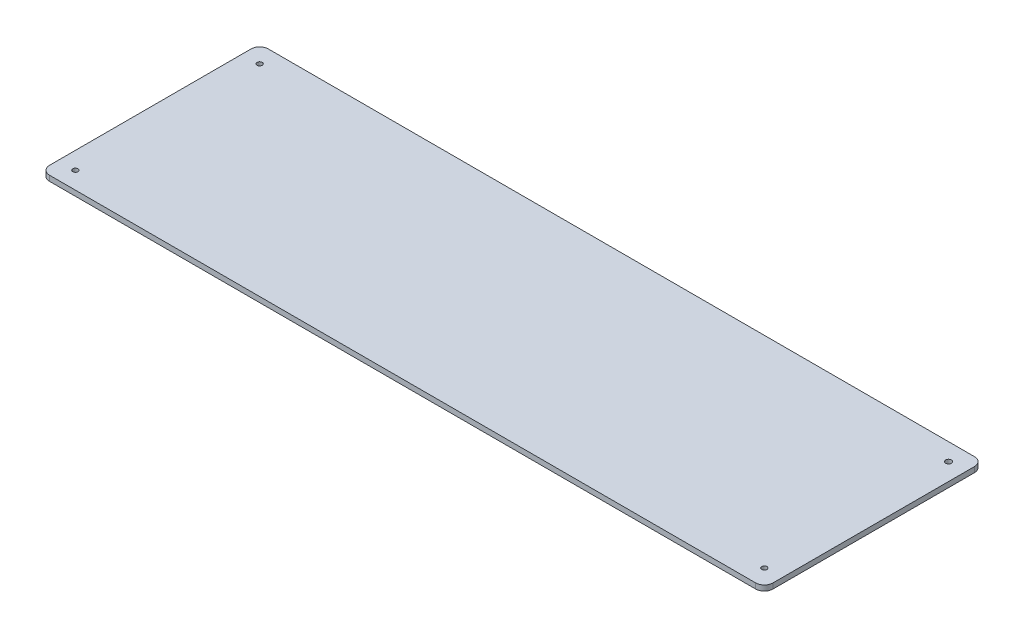
SolidWorks part; units mm, degrees
material "Thornel Mat VMA"
ref_plane "Front Plane" through (0, 0, 0) normal (0, 0, 1) x (1, 0, 0)
ref_plane "Top Plane" through (0, 0, 0) normal (0, 1, 0) x (1, 0, 0)
ref_plane "Right Plane" through (0, 0, 0) normal (1, 0, 0) x (0, 0, -1)
sketch "Sketch1" plane through (0, 0, 0) normal (0, 1, 0) x (1, 0, 0)
  line L1 (-210, -63.5) -> (210, -63.5)
  line L2 (-210, -63.5) -> (-210, 63.5)
  line L3 (-210, 63.5) -> (210, 63.5)
  line L4 (210, -63.5) -> (210, 63.5)
  line L5 (-210, -63.5) -> (210, 63.5) construction
  line L6 (-210, 63.5) -> (210, -63.5) construction
  point P0 (0, 0)
  dimension "D1" = 127
  dimension "D2" = 420
extrude "Boss-Extrude1" add sketch "Sketch1" along normal blind 3.1
fillet "Fillet1" radius 5 4 edges at (210, 1.55, -63.5) (210, 1.55, 63.5) (-210, 1.55, -63.5) (-210, 1.55, 63.5)
sketch "Sketch3" plane through (0, 3.1, 0) normal (0, 1, 0) x (1, 0, 0)
  line L0 (-210, 58.5) -> (-210, -58.5) construction
  line L1 (205, 63.5) -> (-205, 63.5) construction
  line L2 (-205, -63.5) -> (205, -63.5) construction
  line L3 (210, -58.5) -> (210, 58.5) construction
  circle A0 centre (-200, 53.5) radius 1.5
  circle A1 centre (-200, -53.5) radius 1.5
  circle A2 centre (200, 53.5) radius 1.6861
  circle A3 centre (200, -53.5) radius 1.5
  dimension "D1" = 10
  dimension "D2" = 10
  dimension "D3" = 3
  dimension "D4" = 10
  dimension "D5" = 10
  dimension "D6" = 3
  dimension "D7" = 10
  dimension "D8" = 10
  dimension "D9" = 3
  dimension "D10" = 10
  dimension "D11" = 10
extrude "Cut-Extrude1" cut sketch "Sketch3" against normal blind 3.1
